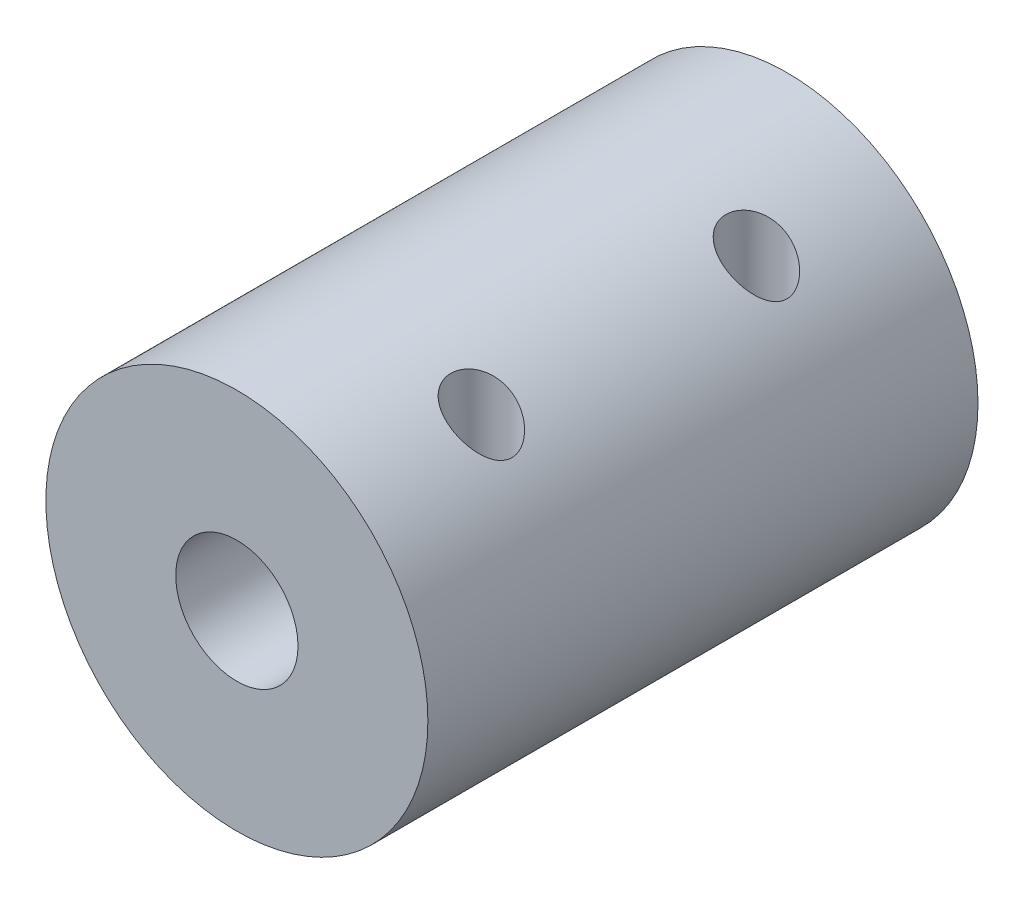
SolidWorks part; units mm, degrees
ref_plane "前视基准面" through (0, 0, 0) normal (0, 0, 1) x (1, 0, 0)
ref_plane "上视基准面" through (0, 0, 0) normal (0, 1, 0) x (1, 0, 0)
ref_plane "右视基准面" through (0, 0, 0) normal (1, 0, 0) x (0, 0, -1)
sketch "草图1" plane through (0, 0, 0) normal (0, 0, 1) x (1, 0, 0)
  circle A0 centre (0, 0) radius 12.5
  dimension "D1" = 25
extrude "拉伸1" add sketch "草图1" along normal blind 36
sketch "草图3" plane through (0, 0, 36) normal (0, 0, 1) x (1, 0, 0)
  circle A0 centre (0, 0) radius 4
  dimension "D1" = 8
extrude "切除-拉伸1" cut sketch "草图3" against normal through all
sketch "草图4" plane through (0, 0, 0) normal (0, 1, 0) x (1, 0, 0)
  line L0 (0, -1000) -> (0, 49000) construction
  line L1 (7, -1000) -> (7, 49000) construction
  line L3 (-1011.1715, -9) -> (48988.8285, -9) construction
  line L4 (-1012.3157, -27) -> (48987.6843, -27) construction
  line L5 (12.5, 0) -> (-12.5, 0) construction
  line L6 (-12.5, -36) -> (12.5, -36) construction
  circle A0 centre (7, -9) radius 2
  circle A1 centre (7, -27) radius 2
  dimension "D4" = 4
  dimension "D5" = 4
  dimension "D1" = 7
  dimension "D2" = 9
  dimension "D3" = 9
extrude "切除-拉伸2" cut sketch "草图4" against normal through all and the other way through all
